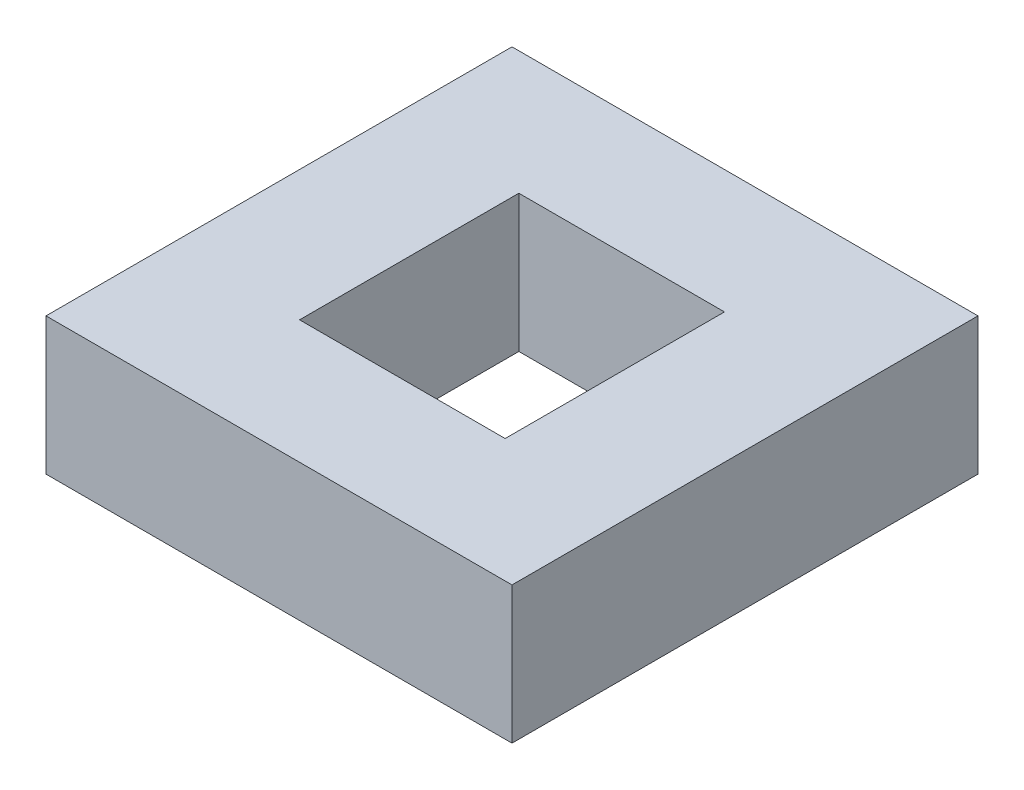
SolidWorks part; units mm, degrees
ref_plane "Front" through (0, 0, 0) normal (0, 0, 1) x (1, 0, 0)
ref_plane "Top" through (0, 0, 0) normal (0, 1, 0) x (1, 0, 0)
ref_plane "Right" through (0, 0, 0) normal (1, 0, 0) x (0, 0, -1)
sketch "Sketch1" plane through (0, 0, 0) normal (0, 1, 0) x (1, 0, 0)
  line L1 (-85, -85) -> (85, -85)
  line L2 (-85, -85) -> (-85, 85)
  line L3 (-85, 85) -> (85, 85)
  line L4 (85, -85) -> (85, 85)
  line L5 (-85, -85) -> (85, 85) construction
  line L6 (-85, 85) -> (85, -85) construction
  point P0 (0, 0)
extrude "Boss-Extrude1" add sketch "Sketch1" along normal blind 50
sketch "Sketch2" plane through (0, 50, 0) normal (0, 1, 0) x (1, 0, 0)
  line L1 (-37.5, -40) -> (37.5, -40)
  line L2 (-37.5, -40) -> (-37.5, 40)
  line L3 (-37.5, 40) -> (37.5, 40)
  line L4 (37.5, -40) -> (37.5, 40)
  line L5 (-37.5, -40) -> (37.5, 40) construction
  line L6 (-37.5, 40) -> (37.5, -40) construction
  point P0 (0, 0)
extrude "Cut-Extrude1" cut sketch "Sketch2" against normal blind 50
